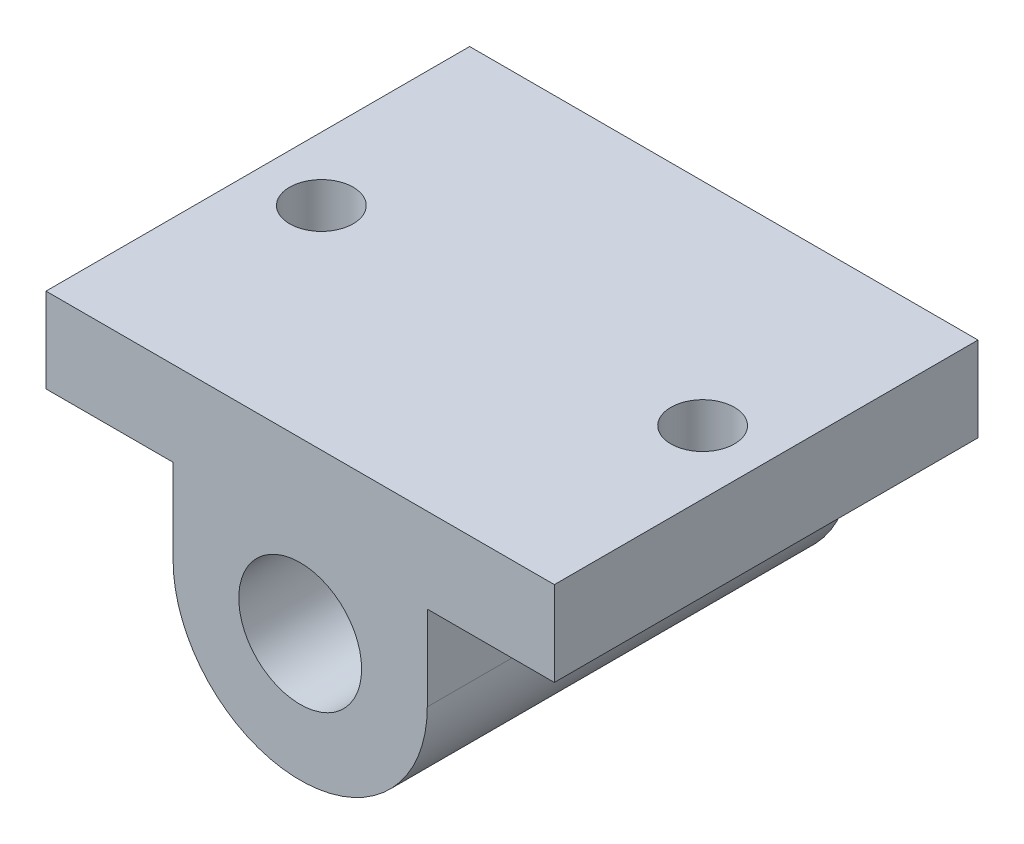
SolidWorks part; units mm, degrees
ref_plane "Plan de face" through (0, 0, 0) normal (0, 0, 1) x (1, 0, 0)
ref_plane "Plan de dessus" through (0, 0, 0) normal (0, 1, 0) x (1, 0, 0)
ref_plane "Plan de droite" through (0, 0, 0) normal (1, 0, 0) x (0, 0, -1)
sketch "Esquisse1" plane through (0, 0, 0) normal (0, 0, 1) x (1, 0, 0)
  line L0 (0, 4) -> (12, 4) construction
  line L1 (12, 4) -> (12, 8) construction
  line L2 (12, 8) -> (-12, 8) construction
  line L3 (-12, 8) -> (-12, 4) construction
  line L4 (-12, 4) -> (0, 4) construction
  line L5 (0, 4) -> (12, 4)
  line L6 (12, 4) -> (12, 8)
  line L7 (12, 8) -> (-12, 8)
  line L8 (-12, 8) -> (-12, 4)
  line L9 (-12, 4) -> (0, 4)
  line L10 (6, 0) -> (6, 4)
  line L11 (-6, 0) -> (-6, 4)
  circle A0 centre (0, 0) radius 4
  circle A1 centre (0, 0) radius 6
  circle A2 centre (0, 0) radius 2.9
  dimension "D1" = 8
  dimension "D2" = 12
  dimension "D6" = 5.8
  dimension "D3" = 12
  dimension "D4" = 12
  dimension "D5" = 4
extrude "Boss.-Extru.1" add sketch "Esquisse1" against normal blind 20 contours A1 L9 L11 | A1 L10 L5 | A1 L5 A0 L9 | L5 A1 L9 | A1 L5 L6 L7 L8 L9
sketch "Esquisse2" plane through (0, 0, 0) normal (0, 0, 1) x (1, 0, 0)
  circle A0 centre (0, 0) radius 2.9
  circle A1 centre (0, 0) radius 4
  dimension "D1" = 5.8
extrude "Boss.-Extru.2" add sketch "Esquisse2" against normal blind 17.5
sketch "Esquisse3" plane through (0, 4, 0) normal (0, -1, 0) x (1, 0, 0)
  line L0 (6, -20) -> (12, 0) construction
  line L1 (12, 0) -> (6, 0) construction
  line L2 (6, 0) -> (12, -20) construction
  line L3 (-6, 0) -> (-12, -20) construction
  line L4 (-12, -20) -> (-6, -20) construction
  line L5 (-6, -20) -> (-12, 0) construction
  circle A0 centre (9, -10) radius 1.5
  circle A1 centre (-9, -10) radius 1.5
  dimension "D1" = 3
  dimension "D2" = 3
extrude "Enlèv. mat.-Extru.1" cut sketch "Esquisse3" against normal blind 17.5
